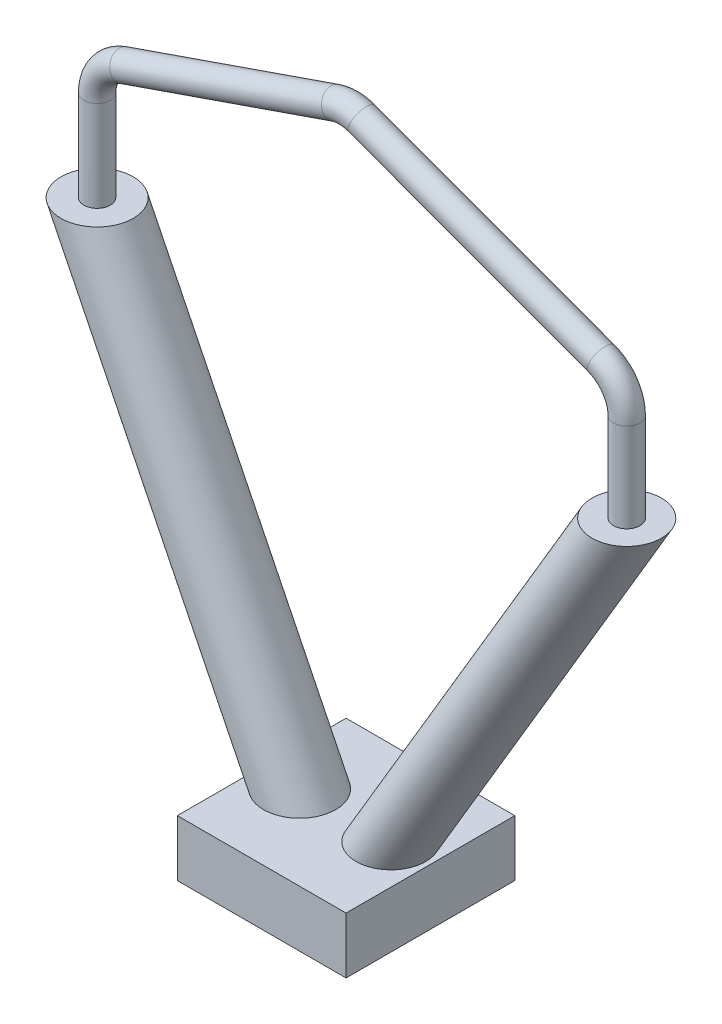
SolidWorks part; units mm, degrees
ref_plane "Alzado" through (0, 0, 0) normal (0, 0, 1) x (1, 0, 0)
ref_plane "Planta" through (0, 0, 0) normal (0, 1, 0) x (1, 0, 0)
ref_plane "Vista lateral" through (0, 0, 0) normal (1, 0, 0) x (0, 0, -1)
sketch "Croquis1" plane through (0, 0, 0) normal (0, 1, 0) x (1, 0, 0)
  line L1 (-150, 150) -> (150, 150)
  line L2 (-150, 150) -> (-150, -150)
  line L3 (-150, -150) -> (150, -150)
  line L4 (150, 150) -> (150, -150)
  line L5 (-150, 150) -> (150, -150) construction
  line L6 (-150, -150) -> (150, 150) construction
  point P0 (0, 0)
  dimension "D1" = 300
  dimension "D2" = 300
extrude "Saliente-Extruir1" add sketch "Croquis1" along normal blind 100
sketch "Croquis2" plane through (0, 100, 0) normal (0, 1, 0) x (1, 0, 0)
  circle A0 centre (79.7197, 0) radius 61.7578
sketch3d "Croquis3D1"
  line L0 (79.7197, 100, 0) -> (499.0174, 807.6577, 0)
sweep "Barrer1" add profiles "Croquis2" path "Croquis3D1"
sketch "Croquis3" plane through (0, 100, 0) normal (0, 1, 0) x (1, 0, 0)
  circle A0 centre (-82.5763, 0) radius 64.1383
sketch3d "Croquis3D2"
  line L0 (-82.5763, 100, 0) -> (-442.6526, 830.3663, 0)
sweep "Barrer2" add profiles "Croquis3" path "Croquis3D2"
ref_plane "Plano1" through (0, 520, 0) normal (0, 1, 0) x (1, 0, 0)
sketch "Croquis5" plane through (0, 807.6577, 0) normal (0, 1, 0) x (1, 0, 0)
  line L0 (79.7197, 0) -> (499.0174, 0) construction
  circle A0 centre (499.0174, 0) radius 23.4986
sketch3d "Croquis3D4"
  line L0 (499.0174, 807.6577, 0) -> (499.0174, 965.7432, 0)
  line L1 (453.1706, 1031.4442, 0) -> (27.9929, 1187.7493, 0)
  line L2 (-442.6526, 830.3663, 0) -> (-442.6526, 991.7492, 0)
  line L3 (-395.5464, 1057.8996, 0) -> (-19.0541, 1188.1987, 0)
  arc A0 (-442.6526, 991.7492, 0) -> (-395.5464, 1057.8996, 0) centre (-372.6526, 991.7492, 0) ccw
  arc A1 (27.9929, 1187.7493, 0) -> (-19.0541, 1188.1987, 0) centre (3.8397, 1122.0483, 0) ccw
  arc A2 (499.0174, 965.7432, 0) -> (453.1706, 1031.4442, 0) centre (429.0174, 965.7432, 0) ccw
  point P9 (-442.6526, 1041.5968, 0)
  point P10 (-372.6526, 991.7492, -70)
  point P13 (4.5496, 1196.3676, 0)
  point P14 (3.8397, 1122.0483, 70)
  point P17 (499.0174, 1014.5899, 0)
  point P18 (429.0174, 965.7432, 70)
  dimension "D1" = 70
sweep "Barrer4" add profiles "Croquis5" path "Croquis3D4"
